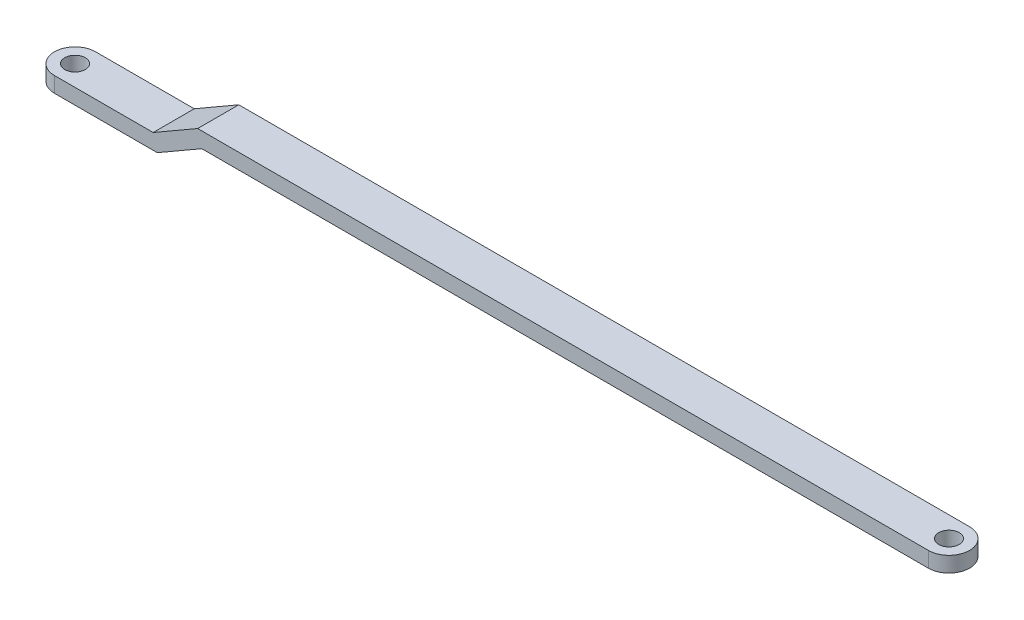
SolidWorks part; units mm, degrees
ref_plane "Front Plane" through (0, 0, 0) normal (0, 0, 1) x (1, 0, 0)
ref_plane "Top Plane" through (0, 0, 0) normal (0, 1, 0) x (1, 0, 0)
ref_plane "Right Plane" through (0, 0, 0) normal (1, 0, 0) x (0, 0, -1)
sketch "Sketch1" plane through (0, 0, 0) normal (0, 1, 0) x (1, 0, 0)
  line L0 (0, 0) -> (170, 0) construction
  line L1 (0, 4) -> (170, 4)
  line L4 (170, -4) -> (0, -4)
  circle A0 centre (0, 0) radius 2
  circle A1 centre (170, 0) radius 2
  circle A2 centre (170, 0) radius 4
  circle A3 centre (0, 0) radius 4
  dimension "D1" = 4
  dimension "D2" = 2
  dimension "D3" = 4
  dimension "D4" = 2
  dimension "D7" = 170
extrude "Boss-Extrude1" add sketch "Sketch1" along normal blind 8
sketch "Sketch2" plane through (0, 0, 4) normal (0, 0, 1) x (1, 0, 0)
  line L0 (-4, 5) -> (174, 5)
  line L1 (-4, 8) -> (174, 8)
  line L2 (-4, 8) -> (-4, 0)
  line L3 (-4, 0) -> (174, 0)
  line L4 (174, 8) -> (174, 0)
  line L5 (174, 3) -> (-4, 3)
  line L6 (16, 0) -> (29.8564, 8) construction
  line L7 (14, 0) -> (27.8564, 8)
  line L8 (20, 0) -> (33.8564, 8)
  line M5 (0, 0) -> (170, 0)
  line M6 (170, 0) -> (170, 8)
  line M8 (0, 8) -> (0, 0)
  dimension "D1" = 3
  dimension "D2" = 3
  dimension "D3" = 30
  dimension "D4" = 20
  dimension "D5" = 1
  dimension "D6" = 3
extrude "Cut-Extrude1" cut sketch "Sketch2" against normal blind 8 contours L5 L7 L0 M8 | L5 L0 L2 M8 | L1 L2 L0 M8 | L0 L7 L1 M8 | L8 L5 M5 M6 | L8 L5 L0 M6 | L5 L4 L0 M6 | L4 L5 L3 M6
